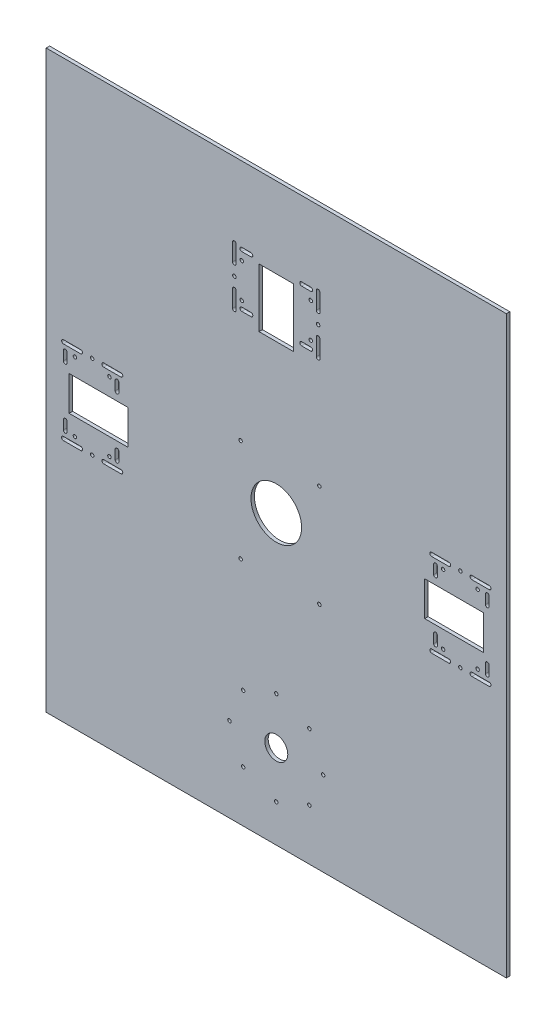
SolidWorks part; units mm, degrees
ref_plane "前视基准面" through (0, 0, 0) normal (0, 0, 1) x (1, 0, 0)
ref_plane "上视基准面" through (0, 0, 0) normal (0, 1, 0) x (1, 0, 0)
ref_plane "右视基准面" through (0, 0, 0) normal (1, 0, 0) x (0, 0, -1)
sketch "草图1" plane through (0, 0, 0) normal (0, 0, 1) x (1, 0, 0)
  line L0 (0, -42.2095) -> (0, 42.2095) construction
  line L1 (200, -250) -> (-200, -250)
  line L2 (200, -250) -> (200, 250)
  line L3 (200, 250) -> (-200, 250)
  line L4 (-200, -250) -> (-200, 250)
  line L5 (200, -250) -> (-200, 250) construction
  line L6 (200, 250) -> (-200, -250) construction
  line L7 (43, 190) -> (-43, 190)
  line L8 (-43, 190) -> (-43, 130)
  line L9 (-43, 130) -> (-37, 124)
  line L10 (-37, 124) -> (37, 124)
  line L11 (-36.4, 185) -> (-36.4, 170) construction
  line L12 (-34.8, 185) -> (-34.8, 170)
  line L13 (-38, 185) -> (-38, 170)
  line L14 (-36.4, 135) -> (-36.4, 150) construction
  line L15 (-38, 135) -> (-38, 150)
  line L16 (-34.8, 135) -> (-34.8, 150)
  line L17 (-22, 183.4) -> (-30, 183.4) construction
  line L18 (-22, 181.8) -> (-30, 181.8)
  line L19 (-22, 185) -> (-30, 185)
  line L20 (-30, 138.4) -> (-22, 138.4) construction
  line L21 (-30, 140) -> (-22, 140)
  line L22 (-30, 136.8) -> (-22, 136.8)
  line L23 (30, 138.4) -> (22, 138.4) construction
  line L24 (30, 140) -> (22, 140)
  line L25 (30, 136.8) -> (22, 136.8)
  line L26 (36.4, 135) -> (36.4, 150) construction
  line L27 (38, 135) -> (38, 150)
  line L28 (34.8, 135) -> (34.8, 150)
  line L29 (36.4, 185) -> (36.4, 170) construction
  line L30 (34.8, 185) -> (34.8, 170)
  line L31 (38, 185) -> (38, 170)
  line L32 (22, 183.4) -> (30, 183.4) construction
  line L33 (22, 181.8) -> (30, 181.8)
  line L34 (22, 185) -> (30, 185)
  line L35 (43, 190) -> (43, 130)
  line L36 (43, 130) -> (37, 124)
  line L37 (124, 37) -> (124, -37)
  line L38 (15, 129) -> (-15, 129)
  line L39 (15, 129) -> (15, 180)
  line L40 (15, 180) -> (-15, 180)
  line L41 (-15, 129) -> (-15, 180)
  line L42 (15, 129) -> (-15, 180) construction
  line L43 (15, 180) -> (-15, 129) construction
  line L44 (130, -43) -> (124, -37)
  line L45 (190, -43) -> (130, -43)
  line L46 (190, -43) -> (190, 43)
  line L47 (129, -15) -> (180, -15)
  line L48 (129, 15) -> (180, 15)
  line L49 (180, -15) -> (180, 15)
  line L50 (129, -15) -> (129, 15)
  line L51 (190, 43) -> (130, 43)
  line L52 (130, 43) -> (124, 37)
  line L53 (185, 36.4) -> (170, 36.4) construction
  line L54 (185, 34.8) -> (170, 34.8)
  line L55 (185, 38) -> (170, 38)
  line L56 (135, 36.4) -> (150, 36.4) construction
  line L57 (135, 38) -> (150, 38)
  line L58 (135, 34.8) -> (150, 34.8)
  line L59 (183.4, 22) -> (183.4, 30) construction
  line L60 (181.8, 22) -> (181.8, 30)
  line L61 (185, 22) -> (185, 30)
  line L62 (138.4, 30) -> (138.4, 22) construction
  line L63 (140, 30) -> (140, 22)
  line L64 (136.8, 30) -> (136.8, 22)
  line L65 (138.4, -30) -> (138.4, -22) construction
  line L66 (140, -30) -> (140, -22)
  line L67 (136.8, -30) -> (136.8, -22)
  line L68 (135, -36.4) -> (150, -36.4) construction
  line L69 (135, -38) -> (150, -38)
  line L70 (135, -34.8) -> (150, -34.8)
  line L71 (185, -36.4) -> (170, -36.4) construction
  line L72 (185, -34.8) -> (170, -34.8)
  line L73 (185, -38) -> (170, -38)
  line L74 (183.4, -22) -> (183.4, -30) construction
  line L75 (181.8, -22) -> (181.8, -30)
  line L76 (185, -22) -> (185, -30)
  line L111 (-124, -37) -> (-124, 37)
  line L112 (-130, 43) -> (-124, 37)
  line L113 (-190, 43) -> (-130, 43)
  line L114 (-190, 43) -> (-190, -43)
  line L115 (-129, 15) -> (-180, 15)
  line L116 (-129, -15) -> (-180, -15)
  line L117 (-180, 15) -> (-180, -15)
  line L118 (-129, 15) -> (-129, -15)
  line L119 (-190, -43) -> (-130, -43)
  line L120 (-130, -43) -> (-124, -37)
  line L121 (-185, -36.4) -> (-170, -36.4) construction
  line L122 (-185, -34.8) -> (-170, -34.8)
  line L123 (-185, -38) -> (-170, -38)
  line L124 (-135, -36.4) -> (-150, -36.4) construction
  line L125 (-135, -38) -> (-150, -38)
  line L126 (-135, -34.8) -> (-150, -34.8)
  line L127 (-183.4, -22) -> (-183.4, -30) construction
  line L128 (-181.8, -22) -> (-181.8, -30)
  line L129 (-185, -22) -> (-185, -30)
  line L130 (-138.4, -30) -> (-138.4, -22) construction
  line L131 (-140, -30) -> (-140, -22)
  line L132 (-136.8, -30) -> (-136.8, -22)
  line L133 (-138.4, 30) -> (-138.4, 22) construction
  line L134 (-140, 30) -> (-140, 22)
  line L135 (-136.8, 30) -> (-136.8, 22)
  line L136 (-135, 36.4) -> (-150, 36.4) construction
  line L137 (-135, 38) -> (-150, 38)
  line L138 (-135, 34.8) -> (-150, 34.8)
  line L139 (-185, 36.4) -> (-170, 36.4) construction
  line L140 (-185, 34.8) -> (-170, 34.8)
  line L141 (-185, 38) -> (-170, 38)
  line L142 (-183.4, 22) -> (-183.4, 30) construction
  line L143 (-181.8, 22) -> (-181.8, 30)
  line L144 (-185, 22) -> (-185, 30)
  line L145 (37, -124) -> (-37, -124) [skipped]
  line L146 (-43, -130) -> (-37, -124) [skipped]
  line L147 (-43, -190) -> (-43, -130) [skipped]
  line L148 (-43, -190) -> (43, -190) [skipped]
  line L149 (43, -190) -> (43, -130) [skipped]
  line L150 (43, -130) -> (37, -124) [skipped]
  line L151 (-15, -129) -> (-15, -180) [skipped]
  line L152 (-15, -180) -> (15, -180) [skipped]
  line L153 (15, -129) -> (15, -180) [skipped]
  line L154 (-15, -129) -> (15, -129) [skipped]
  line L276 (-36.4, -185) -> (-36.4, -170) construction
  line L277 (-38, -185) -> (-38, -170) [skipped]
  line L278 (-34.8, -185) -> (-34.8, -170) [skipped]
  line L279 (30, -138.4) -> (22, -138.4) construction
  line L280 (30, -140) -> (22, -140) [skipped]
  line L281 (30, -136.8) -> (22, -136.8) [skipped]
  line L282 (-22, -183.4) -> (-30, -183.4) construction
  line L283 (-22, -185) -> (-30, -185) [skipped]
  line L284 (-22, -181.8) -> (-30, -181.8) [skipped]
  line L285 (36.4, -185) -> (36.4, -170) construction
  line L286 (34.8, -185) -> (34.8, -170) [skipped]
  line L287 (38, -185) -> (38, -170) [skipped]
  line L288 (36.4, -135) -> (36.4, -150) construction
  line L289 (38, -135) -> (38, -150) [skipped]
  line L290 (34.8, -135) -> (34.8, -150) [skipped]
  line L291 (-30, -138.4) -> (-22, -138.4) construction
  line L292 (-30, -136.8) -> (-22, -136.8) [skipped]
  line L293 (-30, -140) -> (-22, -140) [skipped]
  line L294 (22, -183.4) -> (30, -183.4) construction
  line L295 (22, -181.8) -> (30, -181.8) [skipped]
  line L296 (22, -185) -> (30, -185) [skipped]
  line L297 (-36.4, -135) -> (-36.4, -150) construction
  line L298 (-34.8, -135) -> (-34.8, -150) [skipped]
  line L299 (-38, -135) -> (-38, -150) [skipped]
  line L300 (-36.4, -185) -> (-36.4, -170) construction
  line L301 (-38, -185) -> (-38, -170) [skipped]
  line L302 (-34.8, -185) -> (-34.8, -170) [skipped]
  line L303 (30, -138.4) -> (22, -138.4) construction
  line L304 (30, -140) -> (22, -140) [skipped]
  line L305 (30, -136.8) -> (22, -136.8) [skipped]
  line L306 (-22, -183.4) -> (-30, -183.4) construction
  line L307 (-22, -185) -> (-30, -185) [skipped]
  line L308 (-22, -181.8) -> (-30, -181.8) [skipped]
  line L309 (36.4, -185) -> (36.4, -170) construction
  line L310 (34.8, -185) -> (34.8, -170) [skipped]
  line L311 (38, -185) -> (38, -170) [skipped]
  line L312 (36.4, -135) -> (36.4, -150) construction
  line L313 (38, -135) -> (38, -150) [skipped]
  line L314 (34.8, -135) -> (34.8, -150) [skipped]
  line L315 (-30, -138.4) -> (-22, -138.4) construction
  line L316 (-30, -136.8) -> (-22, -136.8) [skipped]
  line L317 (-30, -140) -> (-22, -140) [skipped]
  line L318 (22, -183.4) -> (30, -183.4) construction
  line L319 (22, -181.8) -> (30, -181.8) [skipped]
  line L320 (22, -185) -> (30, -185) [skipped]
  line L321 (-36.4, -135) -> (-36.4, -150) construction
  line L322 (-34.8, -135) -> (-34.8, -150) [skipped]
  line L323 (-38, -135) -> (-38, -150) [skipped]
  arc A0 (-34.8, 185) -> (-38, 185) centre (-36.4, 185) ccw
  arc A1 (-38, 170) -> (-34.8, 170) centre (-36.4, 170) ccw
  arc A2 (-38, 135) -> (-34.8, 135) centre (-36.4, 135) ccw
  arc A3 (-34.8, 150) -> (-38, 150) centre (-36.4, 150) ccw
  circle A4 centre (-36.4, 160) radius 1.5
  circle A5 centre (-30, 145) radius 1.5
  circle A6 centre (-30, 175) radius 1.5
  arc A7 (-22, 181.8) -> (-22, 185) centre (-22, 183.4) ccw
  arc A8 (-30, 185) -> (-30, 181.8) centre (-30, 183.4) ccw
  arc A9 (-30, 140) -> (-30, 136.8) centre (-30, 138.4) ccw
  arc A10 (-22, 136.8) -> (-22, 140) centre (-22, 138.4) ccw
  arc A11 (30, 140) -> (30, 136.8) centre (30, 138.4) cw
  arc A12 (22, 136.8) -> (22, 140) centre (22, 138.4) cw
  arc A13 (38, 135) -> (34.8, 135) centre (36.4, 135) cw
  arc A14 (34.8, 150) -> (38, 150) centre (36.4, 150) cw
  arc A15 (34.8, 185) -> (38, 185) centre (36.4, 185) cw
  arc A16 (38, 170) -> (34.8, 170) centre (36.4, 170) cw
  arc A17 (22, 181.8) -> (22, 185) centre (22, 183.4) cw
  arc A18 (30, 185) -> (30, 181.8) centre (30, 183.4) cw
  circle A19 centre (36.4, 160) radius 1.5
  circle A20 centre (30, 175) radius 1.5
  circle A21 centre (30, 145) radius 1.5
  circle A22 centre (160, -36.4) radius 1.5
  circle A23 centre (145, -30) radius 1.5
  circle A24 centre (175, -30) radius 1.5
  circle A25 centre (160, 36.4) radius 1.5
  circle A26 centre (175, 30) radius 1.5
  circle A27 centre (145, 30) radius 1.5
  arc A28 (185, 34.8) -> (185, 38) centre (185, 36.4) ccw
  arc A29 (170, 38) -> (170, 34.8) centre (170, 36.4) ccw
  arc A30 (135, 38) -> (135, 34.8) centre (135, 36.4) ccw
  arc A31 (150, 34.8) -> (150, 38) centre (150, 36.4) ccw
  arc A32 (181.8, 22) -> (185, 22) centre (183.4, 22) ccw
  arc A33 (185, 30) -> (181.8, 30) centre (183.4, 30) ccw
  arc A34 (140, 30) -> (136.8, 30) centre (138.4, 30) ccw
  arc A35 (136.8, 22) -> (140, 22) centre (138.4, 22) ccw
  arc A36 (140, -30) -> (136.8, -30) centre (138.4, -30) cw
  arc A37 (136.8, -22) -> (140, -22) centre (138.4, -22) cw
  arc A38 (135, -38) -> (135, -34.8) centre (135, -36.4) cw
  arc A39 (150, -34.8) -> (150, -38) centre (150, -36.4) cw
  arc A40 (185, -34.8) -> (185, -38) centre (185, -36.4) cw
  arc A41 (170, -38) -> (170, -34.8) centre (170, -36.4) cw
  arc A42 (181.8, -22) -> (185, -22) centre (183.4, -22) cw
  arc A43 (185, -30) -> (181.8, -30) centre (183.4, -30) cw
  circle A66 centre (-160, 36.4) radius 1.5
  circle A67 centre (-145, 30) radius 1.5
  circle A68 centre (-175, 30) radius 1.5
  circle A69 centre (-160, -36.4) radius 1.5
  circle A70 centre (-175, -30) radius 1.5
  circle A71 centre (-145, -30) radius 1.5
  arc A72 (-185, -34.8) -> (-185, -38) centre (-185, -36.4) ccw
  arc A73 (-170, -38) -> (-170, -34.8) centre (-170, -36.4) ccw
  arc A74 (-135, -38) -> (-135, -34.8) centre (-135, -36.4) ccw
  arc A75 (-150, -34.8) -> (-150, -38) centre (-150, -36.4) ccw
  arc A76 (-181.8, -22) -> (-185, -22) centre (-183.4, -22) ccw
  arc A77 (-185, -30) -> (-181.8, -30) centre (-183.4, -30) ccw
  arc A78 (-140, -30) -> (-136.8, -30) centre (-138.4, -30) ccw
  arc A79 (-136.8, -22) -> (-140, -22) centre (-138.4, -22) ccw
  arc A80 (-140, 30) -> (-136.8, 30) centre (-138.4, 30) cw
  arc A81 (-136.8, 22) -> (-140, 22) centre (-138.4, 22) cw
  arc A82 (-135, 38) -> (-135, 34.8) centre (-135, 36.4) cw
  arc A83 (-150, 34.8) -> (-150, 38) centre (-150, 36.4) cw
  arc A84 (-185, 34.8) -> (-185, 38) centre (-185, 36.4) cw
  arc A85 (-170, 38) -> (-170, 34.8) centre (-170, 36.4) cw
  arc A86 (-181.8, 22) -> (-185, 22) centre (-183.4, 22) cw
  arc A87 (-185, 30) -> (-181.8, 30) centre (-183.4, 30) cw
  circle A90 centre (-30, -145) radius 1.5 [skipped]
  circle A97 centre (30, -145) radius 1.5 [skipped]
  circle A106 centre (30, -175) radius 1.5 [skipped]
  circle A107 centre (-30, -175) radius 1.5 [skipped]
  circle A108 centre (-36.4, -160) radius 1.5 [skipped]
  circle A109 centre (36.4, -160) radius 1.5 [skipped]
  circle A110 centre (0, 0) radius 22
  circle A111 centre (0, -176.6905) radius 10
  circle A112 centre (0, -135.9853) radius 1.5
  circle A113 centre (28.7829, -147.9076) radius 1.5
  circle A114 centre (40.7052, -176.6905) radius 1.5
  circle A115 centre (28.7829, -205.4734) radius 1.5
  circle A116 centre (0, -217.3957) radius 1.5
  circle A117 centre (-28.7829, -205.4734) radius 1.5
  circle A118 centre (-40.7052, -176.6905) radius 1.5
  circle A119 centre (-28.7829, -147.9076) radius 1.5
  arc A217 (-38, -185) -> (-34.8, -185) centre (-36.4, -185) ccw [skipped]
  arc A218 (-34.8, -170) -> (-38, -170) centre (-36.4, -170) ccw [skipped]
  arc A219 (30, -140) -> (30, -136.8) centre (30, -138.4) ccw [skipped]
  arc A220 (22, -136.8) -> (22, -140) centre (22, -138.4) ccw [skipped]
  arc A221 (-22, -185) -> (-22, -181.8) centre (-22, -183.4) ccw [skipped]
  arc A222 (-30, -181.8) -> (-30, -185) centre (-30, -183.4) ccw [skipped]
  arc A223 (34.8, -185) -> (38, -185) centre (36.4, -185) ccw [skipped]
  arc A224 (38, -170) -> (34.8, -170) centre (36.4, -170) ccw [skipped]
  arc A225 (38, -135) -> (34.8, -135) centre (36.4, -135) ccw [skipped]
  arc A226 (34.8, -150) -> (38, -150) centre (36.4, -150) ccw [skipped]
  arc A227 (-30, -136.8) -> (-30, -140) centre (-30, -138.4) ccw [skipped]
  arc A228 (-22, -140) -> (-22, -136.8) centre (-22, -138.4) ccw [skipped]
  arc A229 (22, -181.8) -> (22, -185) centre (22, -183.4) ccw [skipped]
  arc A230 (30, -185) -> (30, -181.8) centre (30, -183.4) ccw [skipped]
  arc A231 (-34.8, -135) -> (-38, -135) centre (-36.4, -135) ccw [skipped]
  arc A232 (-38, -150) -> (-34.8, -150) centre (-36.4, -150) ccw [skipped]
  point P0 (0, 0)
  point P9 (0, 0)
  point P12 (0, 154.5)
  point P13 (0, 250)
  point P17 (-36.4, 177.5)
  point P23 (-36.4, 142.5)
  point P37 (-26, 183.4)
  point P43 (-26, 138.4)
  point P49 (-26, 185)
  point P52 (26, 138.4)
  point P59 (36.4, 142.5)
  point P66 (36.4, 177.5)
  point P73 (26, 183.4)
  point P79 (0, 190)
  point P87 (0, 124)
  point P94 (-36.4, -142.5)
  point P101 (177.5, 36.4)
  point P107 (142.5, 36.4)
  point P121 (183.4, 26)
  point P127 (138.4, 26)
  point P135 (138.4, -26)
  point P142 (142.5, -36.4)
  point P149 (177.5, -36.4)
  point P156 (183.4, -26)
  point P179 (-36.4, -177.5)
  point P186 (26, -138.4)
  point P199 (-26, -183.4)
  point P204 (36.4, -177.5)
  point P213 (36.4, -142.5)
  point P220 (-26, -138.4)
  point P225 (26, -183.4)
  point P249 (0, -176.6905)
  point P257 (-177.5, -36.4)
  point P263 (-142.5, -36.4)
  point P277 (-183.4, -26)
  point P283 (-138.4, -26)
  point P291 (-138.4, 26)
  point P298 (-142.5, 36.4)
  point P305 (-177.5, 36.4)
  point P312 (-183.4, 26)
  point P329 (0, 0)
  point P400 (-36.4, -177.5)
  point P407 (26, -138.4)
  point P414 (-26, -183.4)
  point P421 (36.4, -177.5)
  point P428 (36.4, -142.5)
  point P435 (-26, -138.4)
  point P442 (26, -183.4)
  point P449 (-36.4, -142.5)
  point P456 (-36.4, -177.5)
  point P463 (26, -138.4)
  point P470 (-26, -183.4)
  point P477 (36.4, -177.5)
  point P484 (36.4, -142.5)
  point P491 (-26, -138.4)
  point P498 (26, -183.4)
  point P505 (-36.4, -142.5)
  point P512 (-36.4, -177.5)
  point P519 (26, -138.4)
  point P526 (-26, -183.4)
  point P533 (36.4, -177.5)
  point P540 (36.4, -142.5)
  point P547 (-26, -138.4)
  point P554 (26, -183.4)
  point P561 (-36.4, -142.5)
  point P568 (-36.4, -177.5)
  point P575 (26, -138.4)
  point P582 (-26, -183.4)
  point P589 (36.4, -177.5)
  point P596 (36.4, -142.5)
  point P603 (-26, -138.4)
  point P610 (26, -183.4)
  point P617 (-36.4, -142.5)
  point P624 (-36.4, -177.5)
  point P631 (26, -138.4)
  point P638 (-26, -183.4)
  point P645 (36.4, -177.5)
  point P652 (36.4, -142.5)
  point P659 (-26, -138.4)
  point P666 (26, -183.4)
  point P673 (-36.4, -142.5)
  point P680 (-36.4, -177.5)
  point P687 (26, -138.4)
  point P694 (-26, -183.4)
  point P701 (36.4, -177.5)
  point P708 (36.4, -142.5)
  point P715 (-26, -138.4)
  point P722 (26, -183.4)
  point P729 (-36.4, -142.5)
  dimension "D8" = 3
  dimension "D9" = 3
  dimension "D10" = 3
  dimension "D30" = 3
  dimension "D31" = 20
  dimension "D1" = 400
  dimension "D2" = 500
  dimension "D3" = 60
  dimension "D4" = 66
  dimension "D5" = 37
  dimension "D6" = 43
  dimension "D7" = 60
  dimension "D11" = 15
  dimension "D12" = 30
  dimension "D13" = 15
  dimension "D14" = 15
  dimension "D15" = 3.2
  dimension "D16" = 3.2
  dimension "D17" = 5
  dimension "D18" = 20
  dimension "D19" = 30
  dimension "D20" = 5
  dimension "D21" = 30
  dimension "D22" = 5
  dimension "D23" = 3.2
  dimension "D24" = 8
  dimension "D25" = 45
  dimension "D26" = 10
  dimension "D27" = 5
  dimension "D28" = 30
  dimension "D29" = 4
  dimension "D32" = 8
extrude "凸台-拉伸1" add sketch "草图1" along normal blind 3 contours L4 L1 L2 L3 A119 A118 A117 A116 A115 A114 A113 A112 A111 A110 L120 L119 L114 L113 L112 L111 L52 L51 L46 L45 L44 L37 L35 L36 L10 L9 L8 L7 | L36 L35 L7 L8 L9 L10 A20 L34 A18 L33 A17 L31 A16 L30 A15 L28 A14 L27 A13 L25 A12 L24 A11 L38 L41 L40 L39 A1 L13 A0 L12 A3 L16 A2 L15 A4 A5 A6 A8 | L119 L120 L111 L112 L113 L114 A79 L132 A78 L131 A77 L129 A76 L128 A75 L126 A74 L125 A73 L123 A72 L122 A71 A70 A69 A67 L115 L118 L116 L117 A66 A68 L135 A81 L134 A80 L138 A83 | L51 L52 L37 L44 L45 L46 A35 L64 A34 L63 A33 L61 A32 L60 A31 L58 A30 L57 A29 L55 A28 L54 A27 A26 A25 A23 L47 L50 L48 L49 A22 A24 L67 A37 L66 A36 L70 A39
sketch "草图2" plane through (0, 0, 3) normal (0, 0, 1) x (1, 0, 0)
  line L0 (-200, -250) -> (-200, 250) construction
  line L1 (200, -250) -> (-200, -250) construction
  circle A0 centre (-31, 39.03) radius 1.5
  circle A1 centre (37.45, 39.03) radius 1.5
  circle A2 centre (-31, -50) radius 1.5
  circle A3 centre (37.45, -50) radius 1.5
  dimension "D1" = 89.03
  dimension "D3" = 3
  dimension "D2" = 68.45
  dimension "D4" = 169
  dimension "D5" = 200
extrude "切除-拉伸1" cut sketch "草图2" against normal through all
